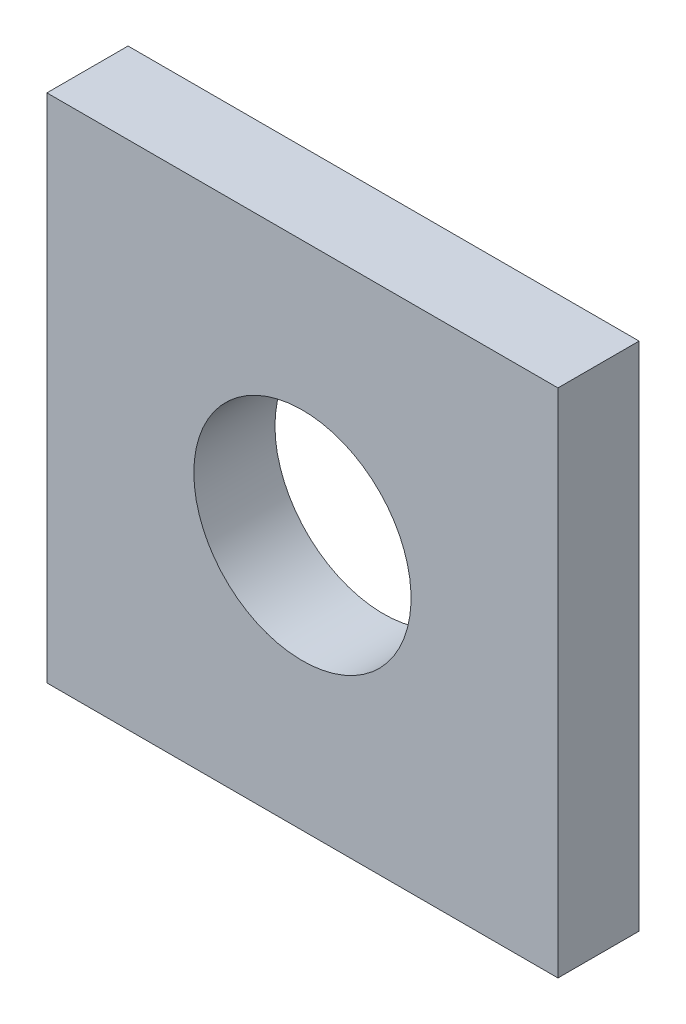
SolidWorks part; units mm, degrees
ref_plane "Front Plane" through (0, 0, 0) normal (0, 0, 1) x (1, 0, 0)
ref_plane "Top Plane" through (0, 0, 0) normal (0, 1, 0) x (1, 0, 0)
ref_plane "Right Plane" through (0, 0, 0) normal (1, 0, 0) x (0, 0, -1)
sketch "Sketch1" plane through (0, 0, 0) normal (0, 0, 1) x (1, 0, 0)
  line L1 (0, 0) -> (20, 0)
  line L2 (0, 0) -> (0, 20)
  line L3 (0, 20) -> (20, 20)
  line L4 (20, 0) -> (20, 20)
  line L5 (0, 0) -> (20, 20) construction
  line L6 (0, 20) -> (20, 0) construction
  point P4 (10, 10)
  dimension "D1" = 20
  dimension "D2" = 20
extrude "Boss-Extrude1" add sketch "Sketch1" along normal blind 3.175
sketch "Sketch2" plane through (0, 0, 0) normal (0, 0, -1) x (-1, 0, 0)
  line L0 (-20, 20) -> (0, 0) construction
  circle A0 centre (-10, 10) radius 4.25
  dimension "D1" = 8.5
extrude "Cut-Extrude1" cut sketch "Sketch2" against normal blind 3.175
